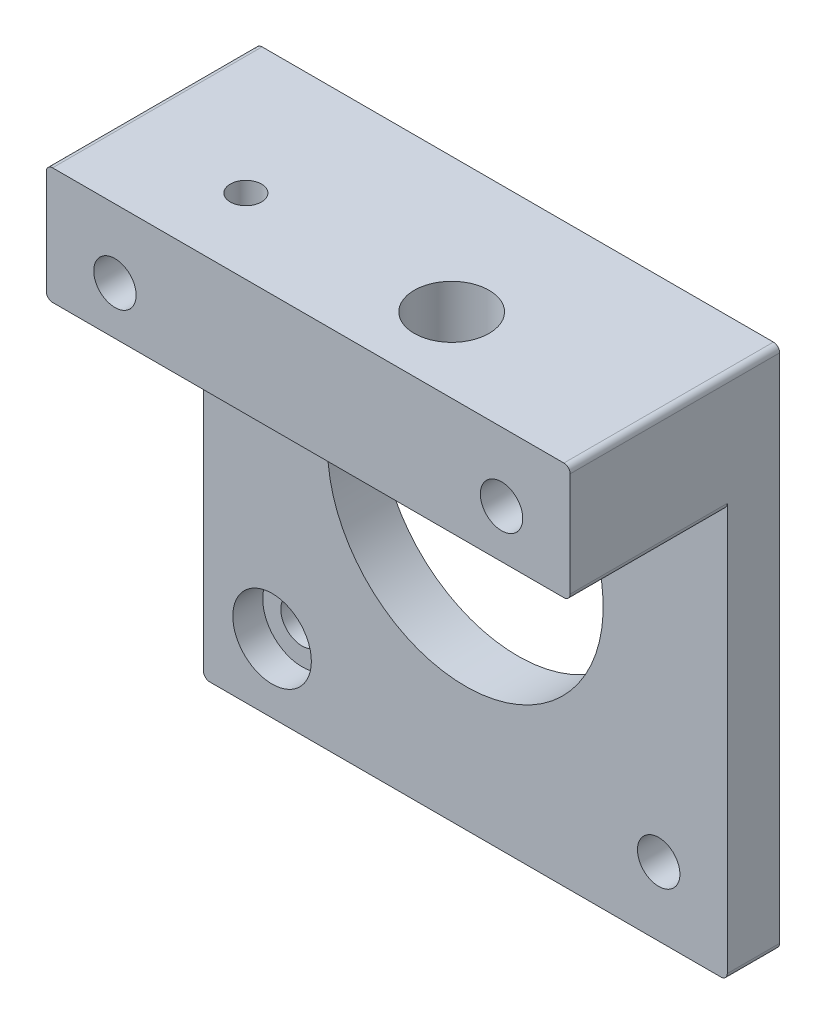
SolidWorks part; units mm, degrees
ref_plane "Front Plane" through (0, 0, 0) normal (0, 0, 1) x (1, 0, 0)
ref_plane "Top Plane" through (0, 0, 0) normal (0, 1, 0) x (1, 0, 0)
ref_plane "Right Plane" through (0, 0, 0) normal (1, 0, 0) x (0, 0, -1)
sketch "Sketch1" plane through (0, 0, 0) normal (0, 0, 1) x (1, 0, 0)
  line L1 (-21, 21) -> (21, 21)
  line L2 (-21, 21) -> (-21, -21)
  line L3 (-21, -21) -> (21, -21)
  line L4 (21, 21) -> (21, -21)
  line L5 (-21, 21) -> (21, -21) construction
  line L6 (-21, -21) -> (21, 21) construction
  point P0 (0, 0)
  dimension "D1" = 42
  dimension "D2" = 42
extrude "Boss-Extrude1" add sketch "Sketch1" along normal blind 16.8
sketch "Sketch2" plane through (0, 0, 16.8) normal (0, 0, 1) x (1, 0, 0)
  line L0 (21, -21) -> (21, 21) construction
  line L1 (-21, -21) -> (21, -21)
  line L2 (-21, -21) -> (-21, 11.65)
  line L3 (-21, 11.65) -> (21, 11.65)
  line L4 (21, -21) -> (21, 11.65)
  line L5 (21, 21) -> (-21, 21) construction
  dimension "D1" = 9.35
extrude "Cut-Extrude1" cut sketch "Sketch2" against normal blind 12.6
sketch "Sketch3" plane through (0, 0, 0) normal (0, 0, -1) x (-1, 0, 0)
  circle A0 centre (0, 0) radius 11.05
  dimension "D1" = 22.1
extrude "Cut-Extrude2" cut sketch "Sketch3" against normal up to next
hole_wizard "M3 Clearance Hole1" positions "Sketch4" profile "Sketch5" hole size "M3" standard "ISO" end condition up to next
sketch "Sketch4" plane through (0, 0, 16.8) normal (0, 0, 1) x (1, 0, 0)
  point P0 (15.5, 15.5)
  point P2 (-15.5, 15.5)
  point P4 (-15.5, -15.5)
  point P6 (15.5, -15.5)
  dimension "D1" = 15.5
  dimension "D2" = 15.5
  dimension "D3" = 15.5
  dimension "D4" = 15.5
sketch "Sketch5" plane through (15.5, 15.5, 16.8) normal (1, 0, 0) x (0, -1, 0)
  line L0 (0, 0) -> (0, 16.8)
  line L1 (0, 16.8) -> (1.7, 16.8)
  line L2 (1.7, 16.8) -> (1.7, 0)
  line L5 (1.7, 0) -> (0, 0)
  line L11 (0, -6.35) -> (0, 107.95) construction
  dimension "Thru Hole Dia." = 3.4
  dimension "Thru Hole Depth" = 16.8
sketch "Sketch6" plane through (0, 0, 4.2) normal (0, 0, 1) x (1, 0, 0)
  circle A0 centre (-15.5, -15.5) radius 3.15
  dimension "D1" = 6.3
extrude "Cut-Extrude3" cut sketch "Sketch6" against normal blind 2.4
hole_wizard "M3 Tapped Hole1" positions "Sketch9" profile "Sketch10" tap size "M3" standard "ISO" end condition up to next
sketch "Sketch9" plane through (0, 21, 0) normal (0, 1, 0) x (1, 0, 0)
  line L0 (-21, -16.8) -> (-21, 0) construction
  line L1 (21, -16.8) -> (-21, -16.8) construction
  point P0 (-11, -10.8)
  dimension "D1" = 10
  dimension "D2" = 6
sketch "Sketch10" plane through (-11, 21, 10.8) normal (1, 0, 0) x (0, 0, 1)
  line L0 (0, 0) -> (0, 9.35)
  line L1 (0, 9.35) -> (1.25, 9.35)
  line L2 (1.25, 9.35) -> (1.25, 0)
  line L5 (1.25, 0) -> (0, 0)
  line L11 (0, -6.35) -> (0, 107.95) construction
  dimension "Thru Tap Drill Dia." = 2.5
  dimension "Thru Tap Drill Depth" = 9.35
cosmetic thread "Hole Thread2" parameters "D2"=3
fillet "Fillet1" radius 0.5 6 edges at (-21, -21, 2.1) (21, -21, 2.1) (21, 21, 8.4) (21, 11.65, 10.5) (-21, 11.65, 10.5) (-21, 21, 8.4)
sketch "Sketch11" plane through (0, 21, 0) normal (0, 1, 0) x (1, 0, 0)
  line L0 (20.5, -16.8) -> (20.5, 0) construction
  line L1 (20.5, -16.8) -> (-20.5, -16.8) construction
  circle A0 centre (5.5, -10.8) radius 3
  dimension "D3" = 6
  dimension "D1" = 15
  dimension "D2" = 6
extrude "Cut-Extrude4" cut sketch "Sketch11" against normal blind 10
